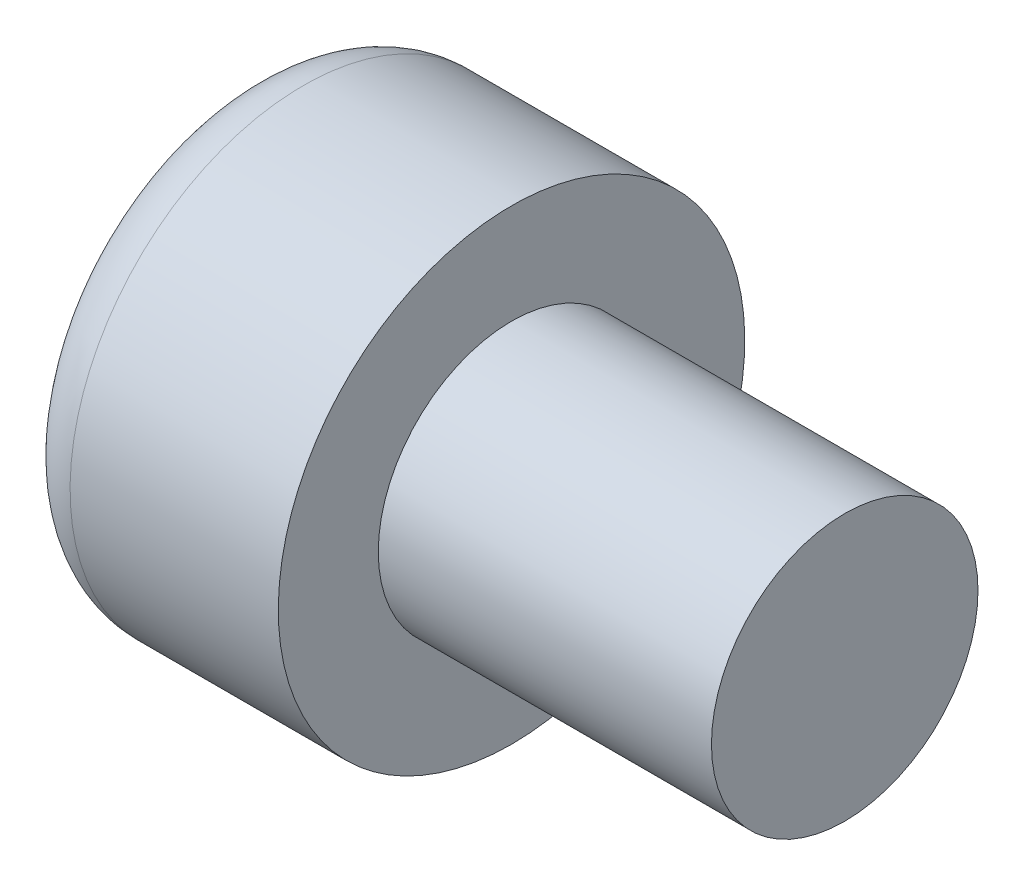
SolidWorks part; units mm, degrees
material "Plain Carbon Steel"
ref_plane "Front Plane" through (0, 0, 0) normal (0, 0, 1) x (1, 0, 0)
ref_plane "Top Plane" through (0, 0, 0) normal (0, 1, 0) x (1, 0, 0)
ref_plane "Right Plane" through (0, 0, 0) normal (1, 0, 0) x (0, 0, -1)
sketch "Sketch1" plane through (0, 0, 0) normal (0, 0, 1) x (1, 0, 0)
  line L0 (0, 0) -> (0, 2.625)
  line L1 (0.875, 3.5) -> (4, 3.5)
  line L2 (4, 3.5) -> (4, 2)
  line L3 (4, 2) -> (9, 2)
  line L4 (9, 2) -> (9, 0)
  line L5 (9, 0) -> (0, 0) construction
  line L6 (0.875, 2.625) -> (0.875, 1.75) construction
  line L7 (0.875, 1.75) -> (0.875, 0.875) construction
  line L8 (0.875, 0.875) -> (0.875, 0) construction
  line L9 (0.875, 3.5) -> (0.875, 2.625) construction
  line L10 (0, 0) -> (9, 0)
  arc A0 (0, 2.625) -> (0.875, 3.5) centre (0.875, 2.625) cw
  dimension "D1" = 4
  dimension "D2" = 7
  dimension "D3" = 4
  dimension "D4" = 5
revolve "Revolve1" add sketch "Sketch1" angle 360 about L10
sketch "Sketch2" plane through (0, 0, 0) normal (-1, 0, 0) x (0, 0, 1)
  line L1 (0, 1.7321) -> (-1.5, 0.866)
  line L2 (-1.5, 0.866) -> (-1.5, -0.866)
  line L3 (-1.5, -0.866) -> (0, -1.7321)
  line L4 (0, -1.7321) -> (1.5, -0.866)
  line L5 (1.5, -0.866) -> (1.5, 0.866)
  line L6 (1.5, 0.866) -> (0, 1.7321)
  circle A0 centre (0, 0) radius 1.5 construction
  dimension "D1" = 3
extrude "Cut-Extrude1" cut sketch "Sketch2" against normal blind 2
